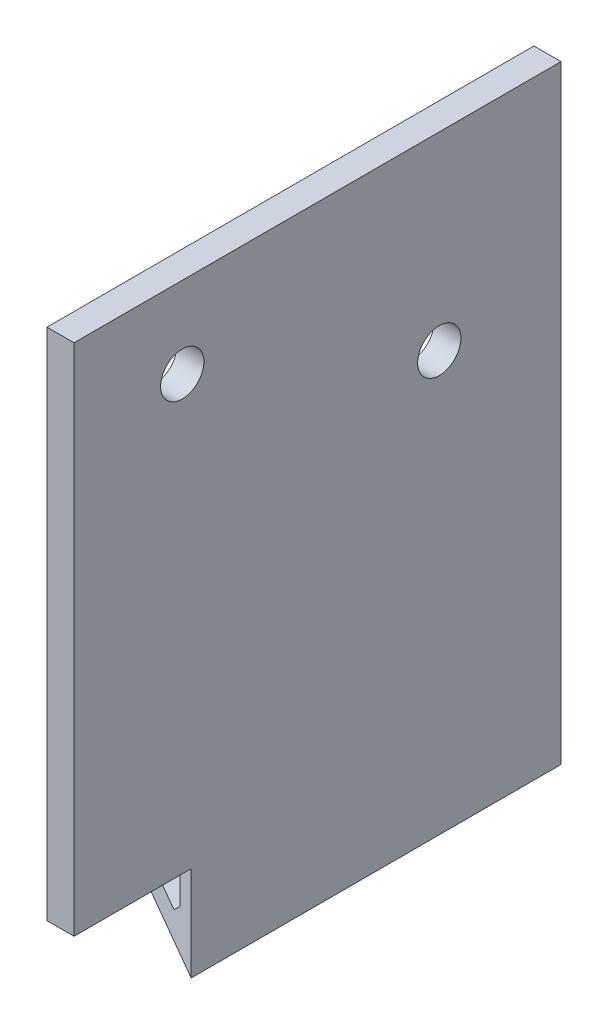
SolidWorks part; units mm, degrees
ref_plane "正面" through (0, 0, 0) normal (0, 0, 1) x (1, 0, 0)
ref_plane "平面" through (0, 0, 0) normal (0, 1, 0) x (1, 0, 0)
ref_plane "右側面" through (0, 0, 0) normal (1, 0, 0) x (0, 0, -1)
sketch "ｽｹｯﾁ2" [suppressed] plane through (0, 0, 0) normal (0, 0, 1) x (1, 0, 0)
  line L0 (0, 0) -> (15, 0)
  line L1 (15, 0) -> (15, 2)
  line L2 (15, 2) -> (2, 2)
  line L3 (2, 2) -> (2, 45)
  line L4 (2, 45) -> (0, 45)
  line L5 (0, 45) -> (0, 0)
  dimension "D1" = 2
  dimension "D2" = 15
  dimension "D3" = 45
extrude "ﾎﾞｽ - 押し出し1" [suppressed] add sketch "ｽｹｯﾁ2" along normal blind 36
sketch "ｽｹｯﾁ3" [suppressed] plane through (0, 0, 0) normal (0, -1, 0) x (1, 0, 0)
  line L0 (7.5, 36) -> (7.5, 18) construction
  line L3 (0, 36) -> (15, 36) construction
  line L4 (7.5, 18) -> (7.5, 8) construction
  line L5 (7.5, 8) -> (7.5, 0) construction
  line L6 (0, 0) -> (15, 0) construction
  circle A0 centre (7.5, 18) radius 1.5
  circle A1 centre (7.5, 8) radius 1.5
  dimension "D1" = 3
  dimension "D2" = 10
  dimension "D3" = 8
extrude "ｶｯﾄ - 押し出し1" [suppressed] cut sketch "ｽｹｯﾁ3" against normal up to next
chamfer "面取り1" [suppressed] distance 1 angle 45
sketch "ｽｹｯﾁ4" [suppressed] plane through (0, 0, 0) normal (-1, 0, 0) x (0, 0, 1)
  line L0 (0, 39) -> (36, 39) construction
  line L1 (0, 45) -> (0, 0) construction
  line L2 (36, 45) -> (36, 0) construction
  line L3 (0, 31) -> (36, 31) construction
  line L4 (9, 45) -> (9, 0) construction
  line L5 (36, 45) -> (0, 45) construction
  line L6 (36, 0) -> (0, 0) construction
  line L7 (28, 0) -> (28, 45) construction
  circle A0 centre (9, 39) radius 1.6
  circle A1 centre (28, 31) radius 1.6
  dimension "D5" = 3.2
  dimension "D1" = 6
  dimension "D2" = 14
  dimension "D3" = 9
  dimension "D4" = 8
extrude "ｶｯﾄ - 押し出し2" [suppressed] cut sketch "ｽｹｯﾁ4" against normal up to next
sketch "ｽｹｯﾁ5" [suppressed] plane through (0, 2, 0) normal (0, 1, 0) x (1, 0, 0)
  line L0 (15, -36) -> (15, -18.6795)
  line L1 (15, -36) -> (15, 0) construction
  line L2 (15, -18.6795) -> (-15, -36)
  line L3 (-15, -36) -> (15, -36)
  dimension "D1" = 30
  dimension "D2" = 30
extrude "ｶｯﾄ - 押し出し3" [suppressed] cut sketch "ｽｹｯﾁ5" against normal through all
sketch "ｽｹｯﾁ10" [suppressed] plane through (0, 2, 0) normal (0, -1, 0) x (1, 0, 0)
  line L8 (0, 27.3397) -> (3, 25.6077)
  line L9 (3, 25.6077) -> (3, 36)
  line L10 (3, 36) -> (0, 36)
  line L11 (0, 36) -> (0, 27.3397)
  line L12 (0, 27.3397) -> (3, 25.6077)
  line L13 (3, 25.6077) -> (3, 36)
  line L14 (3, 36) -> (0, 36)
  line L15 (0, 36) -> (0, 27.3397)
  dimension "D1" = 0
extrude "ｶｯﾄ - 押し出し7" [suppressed] cut sketch "ｽｹｯﾁ10" against normal blind 5
sketch "ｽｹｯﾁ6" plane through (0, 0, 0) normal (0, 0, 1) x (1, 0, 0)
  line L0 (0, 0) -> (15, 0)
  line L1 (15, 0) -> (15, 45)
  line L2 (15, 45) -> (13, 45)
  line L3 (13, 45) -> (13, 2)
  line L4 (13, 2) -> (0, 2)
  line L5 (0, 2) -> (0, 0)
  dimension "D1" = 2
  dimension "D2" = 15
  dimension "D3" = 45
extrude "ﾎﾞｽ - 押し出し2" add sketch "ｽｹｯﾁ6" along normal blind 36
sketch "ｽｹｯﾁ7" plane through (0, 0, 0) normal (0, -1, 0) x (1, 0, 0)
  line L0 (7.5, 36) -> (7.5, 18) construction
  line L1 (0, 36) -> (15, 36) construction
  line L2 (7.5, 18) -> (7.5, 8) construction
  line L3 (7.5, 8) -> (7.5, 0) construction
  line L4 (0, 0) -> (15, 0) construction
  circle A0 centre (7.5, 18) radius 1.5
  circle A1 centre (7.5, 8) radius 1.5
  dimension "D3" = 3
  dimension "D1" = 10
  dimension "D2" = 8
extrude "ｶｯﾄ - 押し出し4" cut sketch "ｽｹｯﾁ7" against normal up to next
chamfer "面取り2" distance 1 angle 45 1 edges at (13, 2, 18)
sketch "ｽｹｯﾁ8" plane through (15, 0, 0) normal (1, 0, 0) x (0, 0, -1)
  line L0 (-36, 39) -> (0, 39) construction
  line L1 (-36, 0) -> (-36, 45) construction
  line L2 (0, 0) -> (0, 45) construction
  line L3 (0, 31) -> (-36, 31) construction
  line L4 (-28, 45) -> (-28, 0) construction
  line L5 (-36, 45) -> (0, 45) construction
  line L6 (-36, 0) -> (0, 0) construction
  line L7 (-9, 0) -> (-9, 45) construction
  circle A0 centre (-28, 39) radius 1.6
  circle A1 centre (-9, 31) radius 1.6
  dimension "D5" = 3.2
  dimension "D1" = 6
  dimension "D2" = 8
  dimension "D3" = 14
  dimension "D4" = 9
extrude "ｶｯﾄ - 押し出し5" cut sketch "ｽｹｯﾁ8" against normal up to next
sketch "ｽｹｯﾁ9" plane through (0, 2, 0) normal (0, 1, 0) x (1, 0, 0)
  line L0 (0, -36) -> (30, -36)
  line L1 (30, -36) -> (0, -18.6795)
  line L2 (0, -36) -> (0, 0) construction
  line L3 (0, -18.6795) -> (0, -36)
  dimension "D1" = 30
  dimension "D2" = 30
extrude "ｶｯﾄ - 押し出し6" cut sketch "ｽｹｯﾁ9" against normal up to next
sketch "ｽｹｯﾁ11" plane through (0, 2, 0) normal (0, -1, 0) x (1, 0, 0)
  line L8 (12, 25.6077) -> (15, 27.3397)
  line L9 (15, 27.3397) -> (15, 36)
  line L10 (15, 36) -> (12, 36)
  line L11 (12, 36) -> (12, 25.6077)
  line L12 (12, 25.6077) -> (15, 27.3397)
  line L13 (15, 27.3397) -> (15, 36)
  line L14 (15, 36) -> (12, 36)
  line L15 (12, 36) -> (12, 25.6077)
  dimension "D1" = 0
extrude "ｶｯﾄ - 押し出し8" cut sketch "ｽｹｯﾁ11" against normal blind 5
